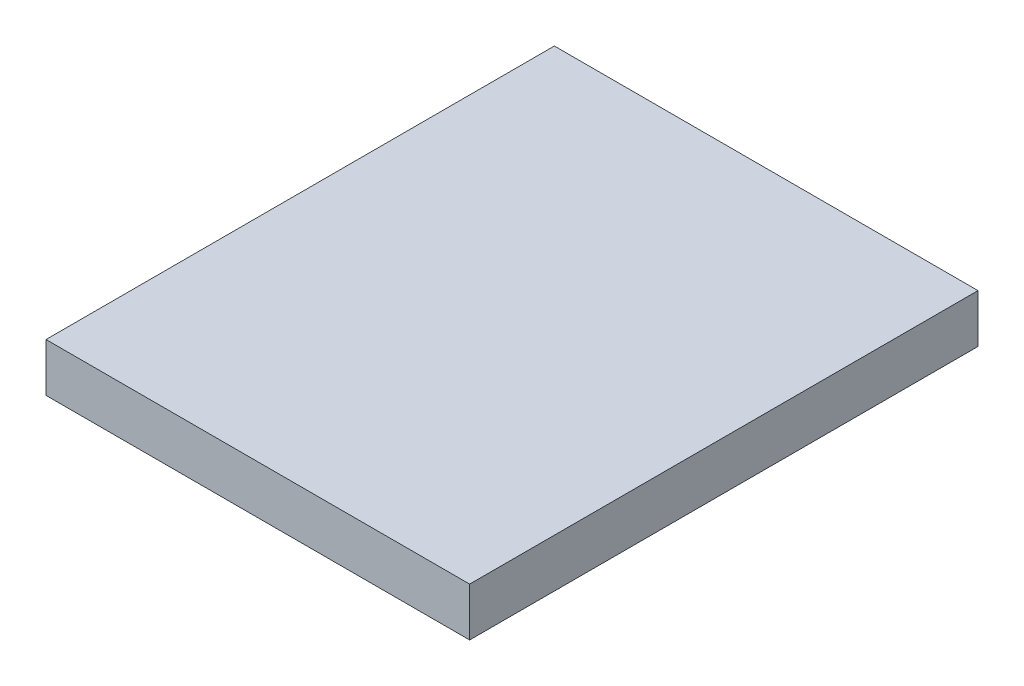
SolidWorks part; units mm, degrees
ref_plane "Front" through (0, 0, 0) normal (0, 0, 1) x (1, 0, 0)
ref_plane "Top" through (0, 0, 0) normal (0, 1, 0) x (1, 0, 0)
ref_plane "Right" through (0, 0, 0) normal (1, 0, 0) x (0, 0, -1)
sketch "Sketch1" plane through (0, 0, 0) normal (0, 1, 0) x (1, 0, 0)
  line L1 (0, 0) -> (35, 0)
  line L2 (0, 0) -> (0, 42)
  line L3 (0, 42) -> (35, 42)
  line L4 (35, 0) -> (35, 42)
  dimension "D1" = 35
  dimension "D2" = 42
extrude "Boss-Extrude1" add sketch "Sketch1" along normal blind 4
